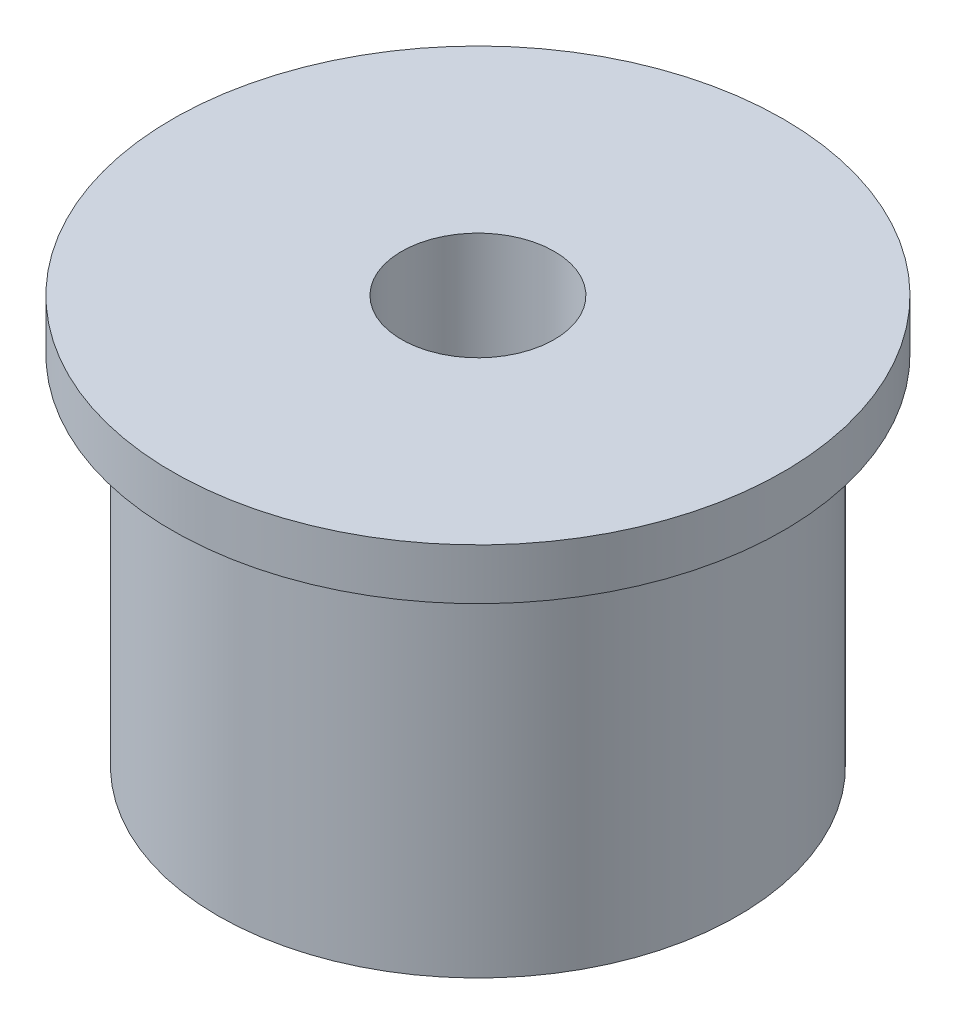
SolidWorks part; units mm, degrees
ref_plane "Front Plane" through (0, 0, 0) normal (0, 0, 1) x (1, 0, 0)
ref_plane "Top Plane" through (0, 0, 0) normal (0, 1, 0) x (1, 0, 0)
ref_plane "Right Plane" through (0, 0, 0) normal (1, 0, 0) x (0, 0, -1)
sketch "Sketch3" plane through (0, 0, 0) normal (0, 0, 1) x (1, 0, 0)
  line L6 (0, 0) -> (0, 47.4743) construction
  line L7 (-4.7625, 0) -> (-4.7625, 25.4)
  line L8 (-4.7625, 25.4) -> (-19.05, 25.4)
  line L9 (-19.05, 25.4) -> (-19.05, 22.225)
  line L10 (-19.05, 22.225) -> (-16.2052, 22.225)
  line L11 (-16.2052, 22.225) -> (-16.2052, 0)
  line L12 (-16.2052, 0) -> (-4.7625, 0)
  dimension "D1" = 4.7625
  dimension "D2" = 19.05
  dimension "D3" = 16.2052
  dimension "D4" = 3.175
  dimension "D5" = 25.4
revolve "Revolve1" add sketch "Sketch3" angle 360 about L6
